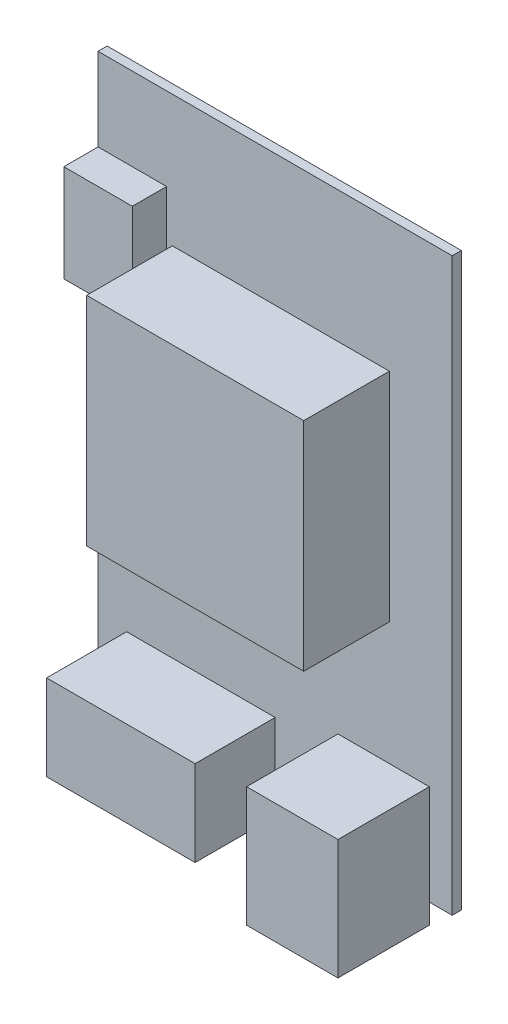
SolidWorks part; units mm, degrees
ref_plane "前视基准面" through (0, 0, 0) normal (0, 0, 1) x (1, 0, 0)
ref_plane "上视基准面" through (0, 0, 0) normal (0, 1, 0) x (1, 0, 0)
ref_plane "右视基准面" through (0, 0, 0) normal (1, 0, 0) x (0, 0, -1)
other "Configuration Table"
sketch "草图1" plane through (0, 0, 0) normal (0, 0, 1) x (1, 0, 0)
  line L0 (-31, -50) -> (31, -50)
  line L1 (31, -50) -> (31, 50)
  line L2 (31, 50) -> (-31, 50)
  line L3 (-31, 50) -> (-31, -50)
extrude "香橙派5_PCB官方外形100x62" add sketch "草图1" along normal blind 1.6
sketch "草图2" plane through (0, 0, 0) normal (0, 0, 1) x (1, 0, 0)
  line L0 (11, -53.5) -> (27, -53.5)
  line L1 (27, -53.5) -> (27, -32.5)
  line L2 (27, -32.5) -> (11, -32.5)
  line L3 (11, -32.5) -> (11, -53.5)
extrude "网口插拔包络_需按实物替换" add sketch "草图2" along normal blind 16 from offset 1.6
sketch "草图3" plane through (0, 0, 0) normal (0, 0, 1) x (1, 0, 0)
  line L0 (-26, -50.5) -> (0, -50.5)
  line L1 (0, -50.5) -> (0, -35.5)
  line L2 (0, -35.5) -> (-26, -35.5)
  line L3 (-26, -35.5) -> (-26, -50.5)
extrude "USB插拔包络_需按实物替换" add sketch "草图3" along normal blind 14 from offset 1.6
sketch "草图4" plane through (0, 0, 0) normal (0, 0, 1) x (1, 0, 0)
  line L0 (-31, 18.5) -> (-19, 18.5)
  line L1 (-19, 18.5) -> (-19, 35.5)
  line L2 (-19, 35.5) -> (-31, 35.5)
  line L3 (-31, 35.5) -> (-31, 18.5)
extrude "电源及视频接口预留" add sketch "草图4" along normal blind 6 from offset 1.6
sketch "草图5" plane through (0, 0, 0) normal (0, 0, 1) x (1, 0, 0)
  line L0 (-18, -11) -> (20, -11)
  line L1 (20, -11) -> (20, 27)
  line L2 (20, 27) -> (-18, 27)
  line L3 (-18, 27) -> (-18, -11)
extrude "散热器及风扇预留_非原厂尺寸" add sketch "草图5" along normal blind 15 from offset 1.6
